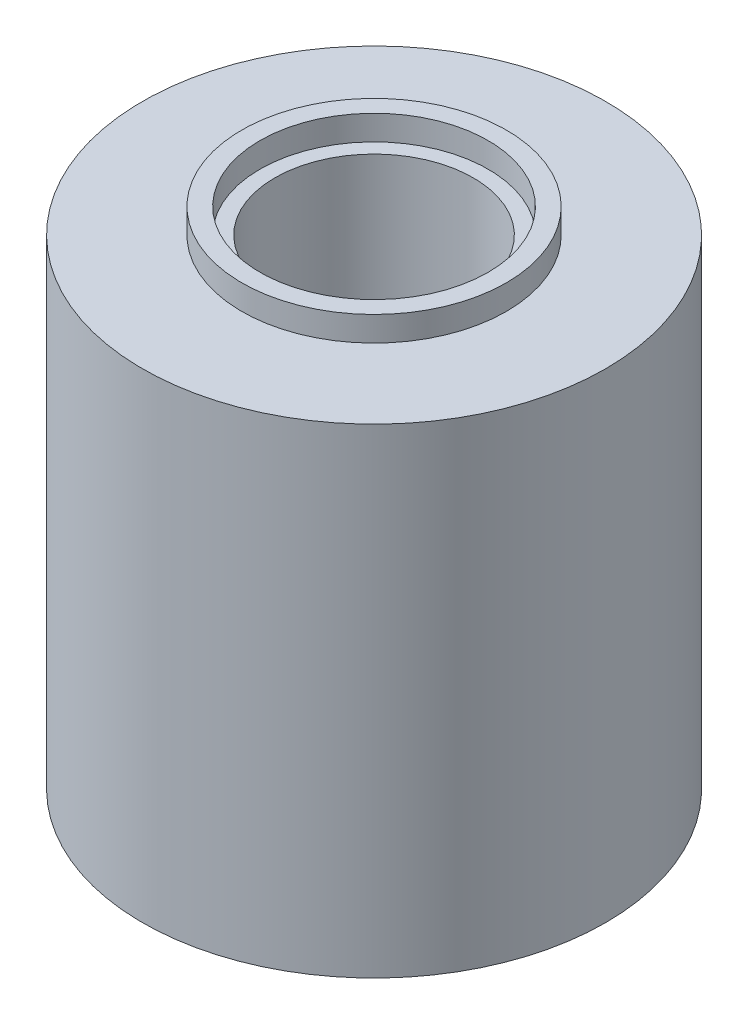
SolidWorks part; units mm, degrees
ref_plane "Plan de face" through (0, 0, 0) normal (0, 0, 1) x (1, 0, 0)
ref_plane "Plan de dessus" through (0, 0, 0) normal (0, 1, 0) x (1, 0, 0)
ref_plane "Plan de droite" through (0, 0, 0) normal (1, 0, 0) x (0, 0, -1)
sketch "Esquisse1" plane through (0, 0, 0) normal (0, 0, 1) x (1, 0, 0)
  line L0 (0, 0) -> (0, 32) construction
  line L1 (8, 0) -> (8, 1.5)
  line L2 (8, 1.5) -> (14, 1.5)
  line L3 (14, 1.5) -> (14, 30.5)
  line L4 (8, 0) -> (6.9, 0)
  line L5 (6.9, 0) -> (6.9, 1.5)
  line L6 (6.9, 1.5) -> (6, 1.5)
  line L7 (6, 1.5) -> (6, 30.5)
  line L8 (14, 16) -> (6, 16) construction
  line L9 (6, 16) -> (0, 16) construction
  line L10 (6.9, 30.5) -> (6, 30.5)
  line L11 (6.9, 32) -> (6.9, 30.5)
  line L12 (8, 32) -> (6.9, 32)
  line L13 (8, 30.5) -> (14, 30.5)
  line L14 (8, 32) -> (8, 30.5)
  dimension "D1" = 13.8
  dimension "D2" = 12
  dimension "D3" = 1.5
  dimension "D4" = 1.5
  dimension "D5" = 16
  dimension "D6" = 28
  dimension "D7" = 32
revolve "Révolution1" add sketch "Esquisse1" angle 360 about L0
